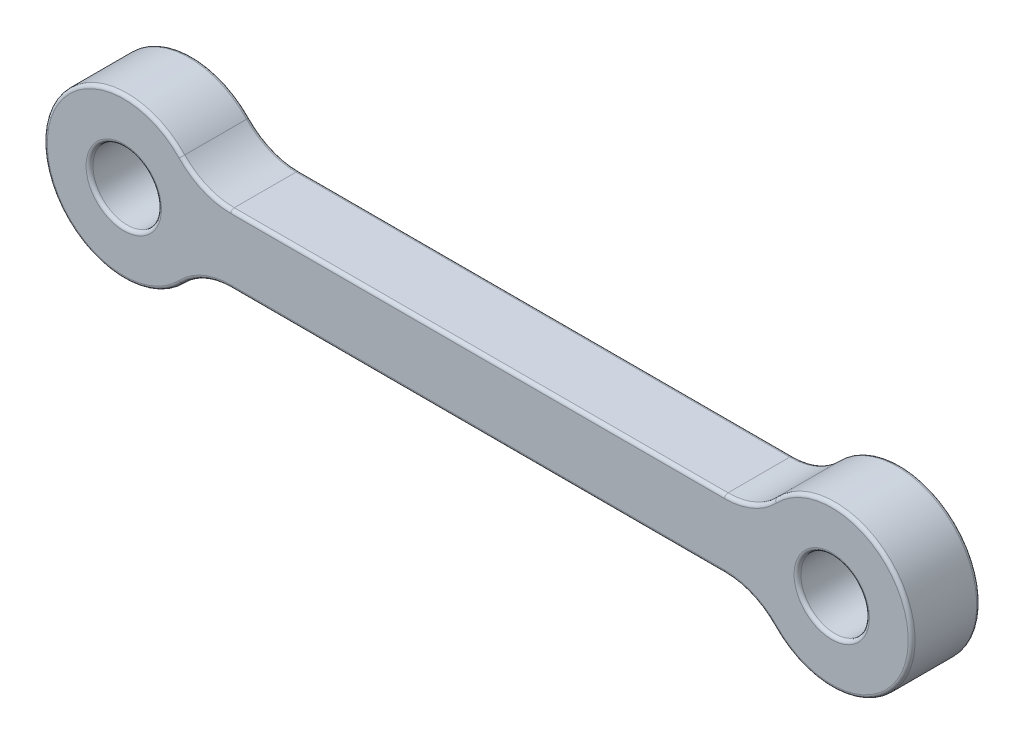
SolidWorks part; units mm, degrees
material "ABS"
ref_plane "Спереди" through (0, 0, 0) normal (0, 0, 1) x (1, 0, 0)
ref_plane "Сверху" through (0, 0, 0) normal (0, 1, 0) x (1, 0, 0)
ref_plane "Справа" through (0, 0, 0) normal (1, 0, 0) x (0, 0, -1)
sketch "Эскиз1" plane through (0, 0, 0) normal (0, 0, 1) x (1, 0, 0)
  line L0 (0, 0) -> (31, 0) construction
  line L1 (0, 3.5) -> (31, 3.5) construction
  line L2 (0, -3.5) -> (31, -3.5) construction
  line L3 (15.5, 0) -> (15.5, -3.5) construction
  line L5 (27.8377, -1.5) -> (3.1623, -1.5)
  line L6 (27.8377, -1.5) -> (27.8377, 1.5) construction
  line L7 (27.8377, 1.5) -> (3.1623, 1.5)
  line L8 (3.1623, -1.5) -> (3.1623, 1.5) construction
  line L9 (27.8377, -1.5) -> (3.1623, 1.5) construction
  line L10 (27.8377, 1.5) -> (3.1623, -1.5) construction
  arc A0 (0, 3.5) -> (0, -3.5) centre (0, 0) ccw construction
  arc A1 (31, -3.5) -> (31, 3.5) centre (31, 0) ccw construction
  circle A2 centre (0, 0) radius 1.5
  circle A3 centre (0, 0) radius 3.5
  circle A4 centre (31, 0) radius 3.5
  circle A5 centre (31, 0) radius 1.5
  point P3 (15.5, 0)
  dimension "D3" = 3
  dimension "D1" = 31
  dimension "D2" = 7
  dimension "D4" = 3
extrude "Бобышка-Вытянуть1" add sketch "Эскиз1" along normal blind 3 contours A3 A2 | L5 A4 L7 A3 | A4 A5
fillet "Скругление1" radius 3 4 edges at (27.8377, 1.5, 1.5) (3.1623, 1.5, 1.5) (27.8377, -1.5, 1.5) (3.1623, -1.5, 1.5)
fillet "Скругление2" radius 0.15 20 edges at (32.5, 0, 0) (3.5137, -1.7404, 0) (15.5, -1.5, 0) (27.4863, -1.7404, 0) (34.5, 0, 0) (27.4863, 1.7404, 0) (15.5, 1.5, 0) (3.5137, 1.7404, 0) (-3.5, 0, 0) (1.5, 0, 0) (32.5, 0, 3) (27.4863, 1.7404, 3) (34.5, 0, 3) (27.4863, -1.7404, 3) (15.5, -1.5, 3) (3.5137, -1.7404, 3) (-3.5, 0, 3) (3.5137, 1.7404, 3) (15.5, 1.5, 3) (1.5, 0, 3)
